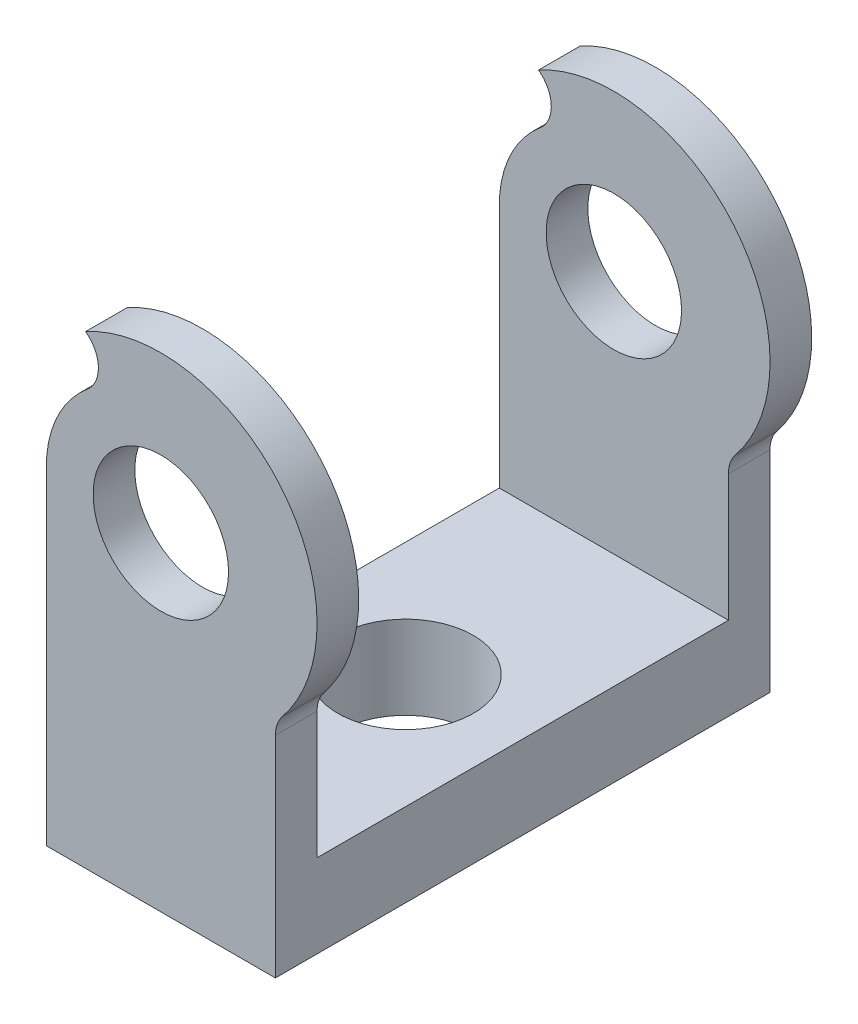
SolidWorks part; units mm, degrees
ref_plane "Front Plane" through (0, 0, 0) normal (0, 0, 1) x (1, 0, 0)
ref_plane "Top Plane" through (0, 0, 0) normal (0, 1, 0) x (1, 0, 0)
ref_plane "Right Plane" through (0, 0, 0) normal (1, 0, 0) x (0, 0, -1)
sketch "Sketch1" plane through (0, 0, 0) normal (0, 0, 1) x (1, 0, 0)
  line L1 (0, 0) -> (22, 0)
  line L2 (0, 0) -> (0, 31.5)
  line L4 (22, 0) -> (22, 21.302)
  arc A2 (3.9234, 39.9215) -> (0, 31.5) centre (11, 31.5) ccw
  arc A3 (22, 21.302) -> (3.7646, 44.6396) centre (11, 31.5) ccw
  arc A4 (3.9234, 39.9215) -> (3.7646, 44.6396) centre (1.9934, 42.2183) ccw
  point P4 (11, 15.75)
  point P8 (1.9986, 42.2275)
  point P10 (0, 0)
  point P11 (0, 0)
  point P12 (0, 0)
  dimension "D1" = 11
  dimension "D2" = 15
  dimension "D3" = 22
  dimension "D4" = 11
  dimension "D5" = 31.5
extrude "Boss-Extrude1" add sketch "Sketch1" along normal blind 4
sketch "Sketch2" plane through (0, 0, 4) normal (0, 0, 1) x (1, 0, 0)
  line L1 (0, 0) -> (22, 0)
  line L2 (0, 0) -> (0, 8)
  line L3 (0, 8) -> (22, 8)
  line L4 (22, 0) -> (22, 8)
  line L5 (0, 0) -> (22, 8) construction
  line L6 (0, 8) -> (22, 0) construction
  point P4 (11, 3.4724)
extrude "Boss-Extrude2" add sketch "Sketch2" along normal blind 39.5
sketch "Sketch3" plane through (0, 0, 43.5) normal (0, 0, 1) x (1, 0, 0)
  line L1 (0, 0) -> (22, 0)
  line L2 (0, 0) -> (0, 31.5)
  line L4 (22, 0) -> (22, 21.302)
  arc A2 (3.9293, 39.9265) -> (0, 31.5) centre (11, 31.5) ccw
  arc A3 (22, 21.302) -> (3.7739, 44.6447) centre (11, 31.5) ccw
  arc A4 (3.9293, 39.9265) -> (3.7739, 44.6447) centre (2.001, 42.2246) ccw
  point P4 (11, 15.75)
  point P8 (0, 0)
  dimension "D1" = 3
extrude "Boss-Extrude3" add sketch "Sketch3" along normal blind 4
fillet "Fillet1" radius 3 2 edges at (22, 21.302, 45.5) (22, 21.302, 2)
sketch "Sketch4" plane through (0, 0, 47.5) normal (0, 0, 1) x (1, 0, 0)
  circle A0 centre (11, 31.5) radius 6.5
extrude "Cut-Extrude1" cut sketch "Sketch4" against normal through all
sketch "Sketch5" plane through (0, 0, 0) normal (0, -1, 0) x (-1, 0, 0)
  circle A0 centre (-11, -24) radius 6.5
extrude "Cut-Extrude2" cut sketch "Sketch5" against normal up to next
